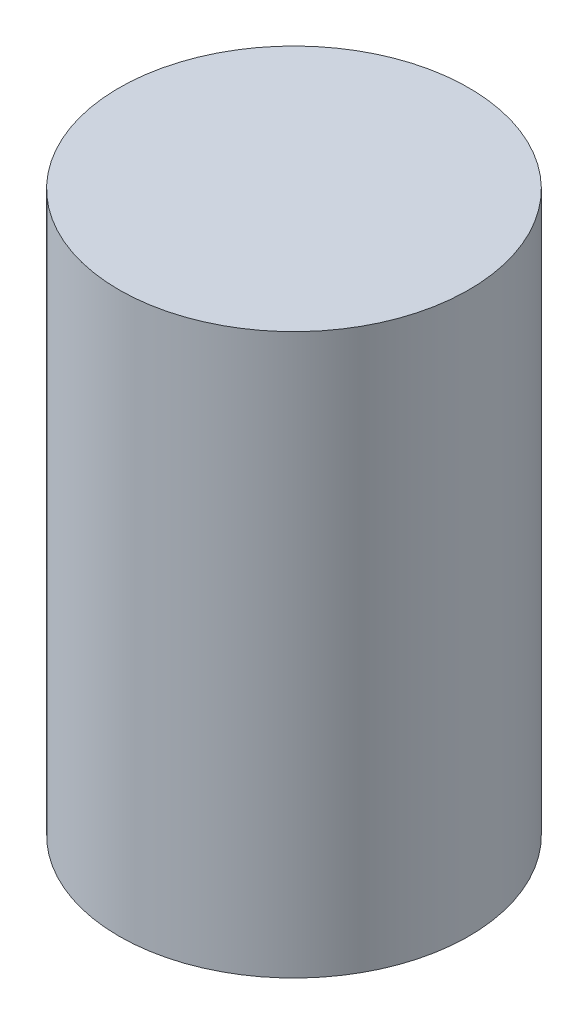
SolidWorks part; units mm, degrees
ref_plane "前视基准面" through (0, 0, 0) normal (0, 0, 1) x (1, 0, 0)
ref_plane "上视基准面" through (0, 0, 0) normal (0, 1, 0) x (1, 0, 0)
ref_plane "右视基准面" through (0, 0, 0) normal (1, 0, 0) x (0, 0, -1)
other "Configuration Table"
sketch "草图1" plane through (0, 0, 0) normal (0, 1, 0) x (1, 0, 0)
  circle A0 centre (0, 0) radius 25
  dimension "D1" = 50
extrude "凸台-拉伸1" add sketch "草图1" along normal blind 80
sketch "草图3" plane through (0, 0, 0) normal (0, -1, 0) x (1, 0, 0)
  circle A0 centre (0, 0) radius 22
  dimension "D1" = 44
extrude "切除-拉伸1" cut sketch "草图3" against normal blind 75
sketch "草图4" plane through (0, 0, 0) normal (0, -1, 0) x (1, 0, 0)
  circle A0 centre (0, 0) radius 22
  circle A1 centre (0, 0) radius 5
  dimension "D1" = 44
  dimension "D2" = 10
extrude "凸台-拉伸2" add sketch "草图4" against normal blind 5
